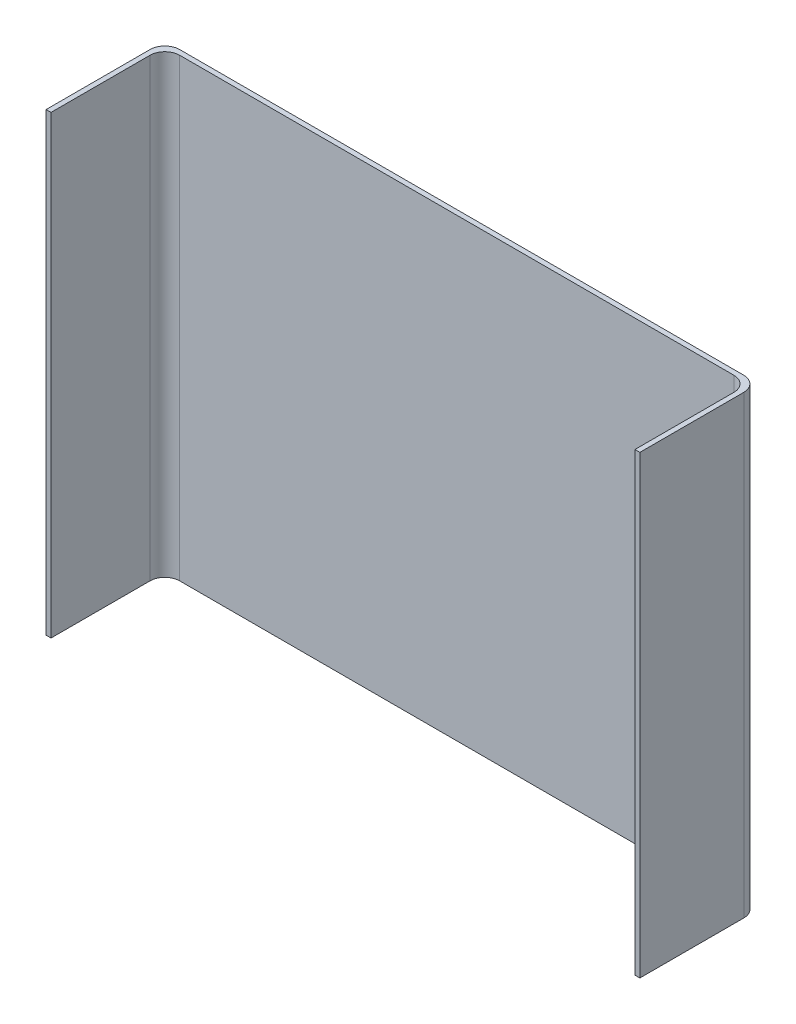
SolidWorks part; units mm, degrees
ref_plane "Front Plane" through (0, 0, 0) normal (0, 0, 1) x (1, 0, 0)
ref_plane "Top Plane" through (0, 0, 0) normal (0, 1, 0) x (1, 0, 0)
ref_plane "Right Plane" through (0, 0, 0) normal (1, 0, 0) x (0, 0, -1)
sketch "Sketch1" plane through (0, 0, 0) normal (0, 0, 1) x (1, 0, 0)
  line L1 (-60, 46) -> (60, 46)
  line L2 (-60, 46) -> (-60, -46)
  line L3 (-60, -46) -> (60, -46)
  line L4 (60, 46) -> (60, -46)
  line L5 (-60, 46) -> (60, -46) construction
  line L6 (-60, -46) -> (60, 46) construction
  point P0 (0, 0)
  dimension "D1" = 92
  dimension "D2" = 120
extrude "Boss-Extrude1" add sketch "Sketch1" along normal blind 1
sketch "Sketch2" plane through (0, 0, 1) normal (0, 0, 1) x (1, 0, 0)
  line L0 (60, 46) -> (-60, 46) construction
  line L1 (-60, -46) -> (-59, -46)
  line L2 (-60, -46) -> (-60, 46)
  line L3 (-60, 46) -> (-59, 46)
  line L4 (-59, -46) -> (-59, 46)
  dimension "D1" = 1
extrude "Boss-Extrude2" add sketch "Sketch2" along normal blind 23
fillet "Fillet1" radius 3 1 edges at (-60, 0, 0)
fillet "Fillet2" radius 3 1 edges at (-59, 0, 1)
mirror "Mirror3" about plane through (0, 0, 0) normal (1, 0, 0) of "Boss-Extrude2"
fillet "Fillet3" radius 3 2 edges at (60, 0, 0) (59, 0, 1)
